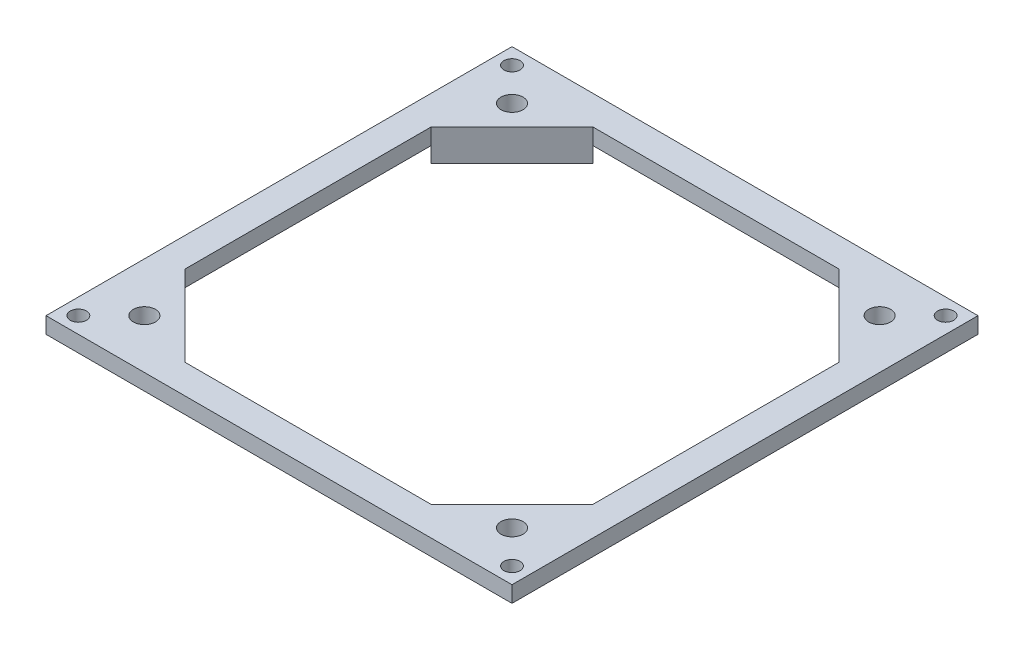
SolidWorks part; units mm, degrees
ref_plane "Front Plane" through (0, 0, 0) normal (0, 0, 1) x (1, 0, 0)
ref_plane "Top Plane" through (0, 0, 0) normal (0, 1, 0) x (1, 0, 0)
ref_plane "Right Plane" through (0, 0, 0) normal (1, 0, 0) x (0, 0, -1)
sketch "Sketch1" plane through (0, 0, 0) normal (0, 1, 0) x (1, 0, 0)
  line L1 (-45.72, -45.72) -> (45.72, -45.72)
  line L2 (-45.72, -45.72) -> (-45.72, 45.72)
  line L3 (-45.72, 45.72) -> (45.72, 45.72)
  line L4 (45.72, -45.72) -> (45.72, 45.72)
  line L5 (-45.72, -45.72) -> (45.72, 45.72) construction
  line L6 (-45.72, 45.72) -> (45.72, -45.72) construction
  point P0 (0, 0)
  dimension "D1" = 91.44
  dimension "D2" = 91.44
extrude "Boss-Extrude1" add sketch "Sketch1" along normal blind 3.175
sketch "Sketch2" plane through (0, 0, 0) normal (0, -1, 0) x (1, 0, 0)
  line L1 (-40.005, -40.005) -> (40.005, -40.005)
  line L2 (-40.005, -40.005) -> (-40.005, 40.005)
  line L3 (-40.005, 40.005) -> (40.005, 40.005)
  line L4 (40.005, -40.005) -> (40.005, 40.005)
  line L5 (-40.005, -40.005) -> (40.005, 40.005) construction
  line L6 (-40.005, 40.005) -> (40.005, -40.005) construction
  point P0 (0, 0)
  dimension "D1" = 80.01
  dimension "D2" = 80.01
extrude "Boss-Extrude2" add sketch "Sketch2" along normal blind 3.048
sketch "Sketch3" plane through (0, -3.048, 0) normal (0, -1, 0) x (1, 0, 0)
  line L0 (-24.13, 40.005) -> (-40.005, 24.13)
  line L1 (40.005, 40.005) -> (-40.005, 40.005) construction
  line L2 (-40.005, 40.005) -> (-40.005, -40.005) construction
  line L3 (-40.005, 24.13) -> (-40.005, -24.13)
  line L4 (-40.005, -24.13) -> (-24.13, -40.005)
  line L5 (-40.005, -40.005) -> (40.005, -40.005) construction
  line L6 (-24.13, -40.005) -> (24.13, -40.005)
  line L7 (-40.005, -40.005) -> (40.005, -40.005) construction
  line L8 (24.13, -40.005) -> (40.005, -24.13)
  line L9 (40.005, -40.005) -> (40.005, 40.005) construction
  line L10 (40.005, -24.13) -> (40.005, 24.13)
  line L11 (40.005, -40.005) -> (40.005, 40.005) construction
  line L12 (40.005, 24.13) -> (24.13, 40.005)
  line L13 (40.005, 40.005) -> (-40.005, 40.005) construction
  line L14 (24.13, 40.005) -> (-24.13, 40.005)
  dimension "D1" = 15.875
  dimension "D2" = 15.875
  dimension "D3" = 15.875
  dimension "D4" = 15.875
  dimension "D5" = 15.875
  dimension "D6" = 15.875
  dimension "D7" = 15.875
extrude "Cut-Extrude1" cut sketch "Sketch3" against normal through all
sketch "Sketch4" plane through (0, -3.048, 0) normal (0, -1, 0) x (1, 0, 0)
  line L0 (-24.13, 40.005) -> (-40.005, 40.005) construction
  line L1 (-40.005, 40.005) -> (-40.005, 24.13) construction
  line L2 (40.005, 40.005) -> (24.13, 40.005) construction
  line L3 (40.005, 24.13) -> (40.005, 40.005) construction
  circle A0 centre (-36.068, 36.068) radius 2.159
  circle A1 centre (36.068, 36.068) radius 2.159
  circle A2 centre (36.068, -36.068) radius 2.159
  circle A3 centre (-36.068, -36.068) radius 2.159
  point P15 (0, 0)
  dimension "D1" = 4.318
  dimension "D2" = 3.937
  dimension "D3" = 3.937
  dimension "D5" = 3.937
  dimension "D6" = 3.937
  dimension "D4" = 4
extrude "Cut-Extrude2" cut sketch "Sketch4" against normal through all
fillet "Fillet1" radius 2.54 4 edges at (-40.005, -1.524, -40.005) (40.005, -1.524, -40.005) (40.005, -1.524, 40.005) (-40.005, -1.524, 40.005)
sketch "Sketch5" plane through (0, 3.175, 0) normal (0, 1, 0) x (1, 0, 0)
  line L0 (45.72, 45.72) -> (-45.72, 45.72) construction
  line L1 (-45.72, 45.72) -> (-45.72, -45.72) construction
  line L2 (45.72, -45.72) -> (45.72, 45.72) construction
  circle A0 centre (-42.545, 42.545) radius 1.5875
  circle A1 centre (42.545, 42.545) radius 1.5875
  circle A2 centre (42.545, -42.545) radius 1.5875
  circle A3 centre (-42.545, -42.545) radius 1.5875
  point P15 (0, 0)
  dimension "D1" = 3.175
  dimension "D2" = 3.175
  dimension "D3" = 3.175
  dimension "D5" = 3.175
  dimension "D6" = 3.175
  dimension "D4" = 4
extrude "Cut-Extrude3" cut sketch "Sketch5" against normal through all
